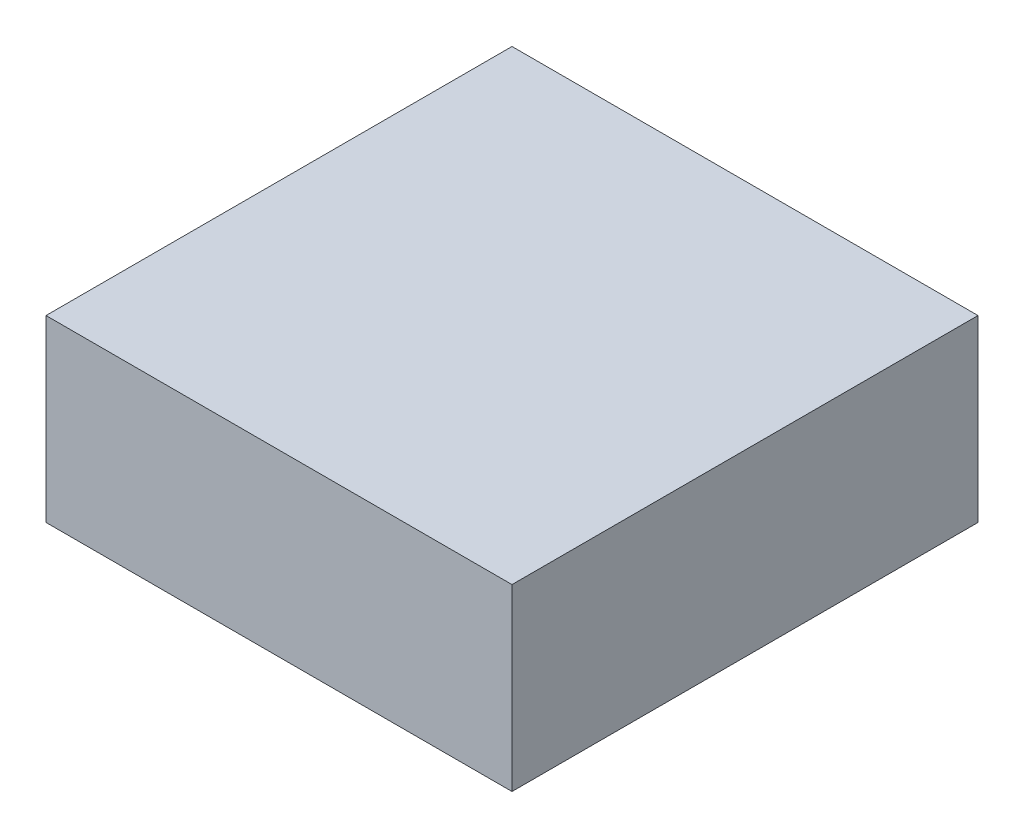
SolidWorks part; units mm, degrees
ref_plane "Front Plane" through (0, 0, 0) normal (0, 0, 1) x (1, 0, 0)
ref_plane "Top Plane" through (0, 0, 0) normal (0, 1, 0) x (1, 0, 0)
ref_plane "Right Plane" through (0, 0, 0) normal (1, 0, 0) x (0, 0, -1)
sketch "Sketch1" plane through (0, 0, 0) normal (0, 1, 0) x (1, 0, 0)
  line L1 (-6.1891, 5.7597) -> (6.8109, 5.7597)
  line L2 (-6.1891, 5.7597) -> (-6.1891, -7.2403)
  line L3 (-6.1891, -7.2403) -> (6.8109, -7.2403)
  line L4 (6.8109, 5.7597) -> (6.8109, -7.2403)
  dimension "D1" = 13
  dimension "D2" = 13
extrude "Boss-Extrude1" add sketch "Sketch1" along normal blind 5
